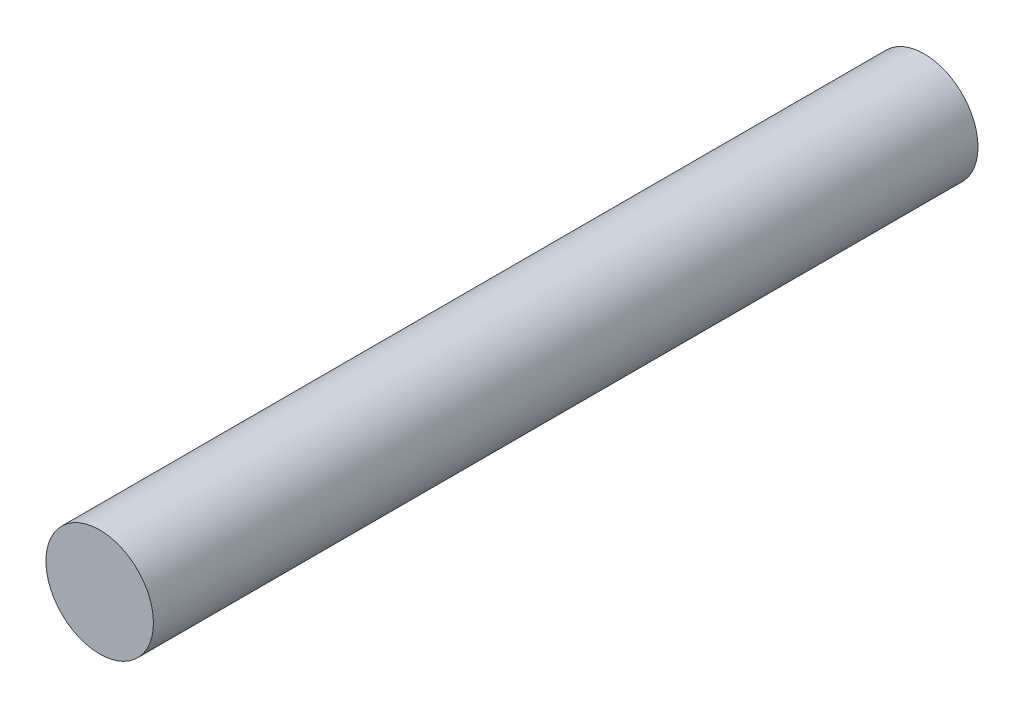
SolidWorks part; units mm, degrees
ref_plane "Front Plane" through (0, 0, 0) normal (0, 0, 1) x (1, 0, 0)
ref_plane "Top Plane" through (0, 0, 0) normal (0, 1, 0) x (1, 0, 0)
ref_plane "Right Plane" through (0, 0, 0) normal (1, 0, 0) x (0, 0, -1)
sketch "Sketch1" plane through (0, 0, 0) normal (0, 0, 1) x (1, 0, 0)
  circle A0 centre (0, 0) radius 15
  dimension "D1" = 30
extrude "Boss-Extrude1" add sketch "Sketch1" along normal blind 230
